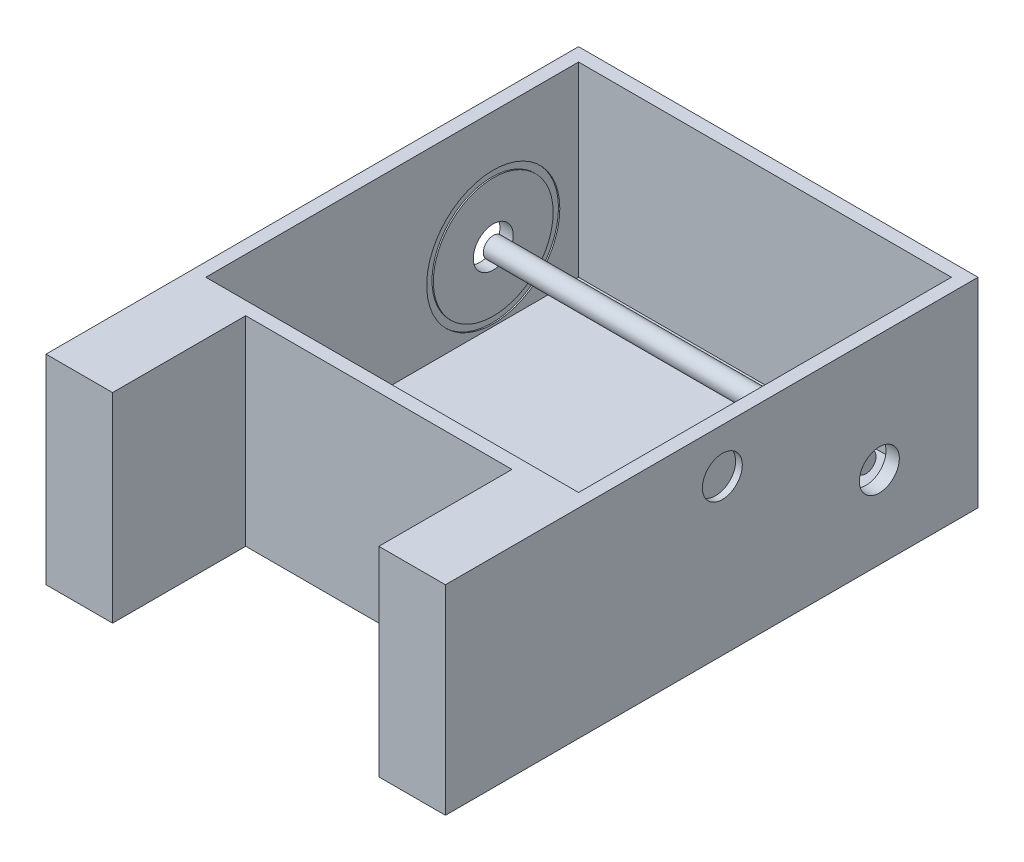
SolidWorks part; units mm, degrees
ref_plane "Front Plane" through (0, 0, 0) normal (0, 0, 1) x (1, 0, 0)
ref_plane "Top Plane" through (0, 0, 0) normal (0, 1, 0) x (1, 0, 0)
ref_plane "Right Plane" through (0, 0, 0) normal (1, 0, 0) x (0, 0, -1)
sketch "Sketch1" plane through (0, 0, 0) normal (0, 0, 1) x (1, 0, 0)
  line L1 (-150, -75) -> (150, -75)
  line L2 (-150, -75) -> (-150, 75)
  line L3 (-150, 75) -> (150, 75)
  line L4 (150, -75) -> (150, 75)
  line L5 (-150, -75) -> (150, 75) construction
  line L6 (-150, 75) -> (150, -75) construction
  point P0 (0, 0)
  dimension "D1" = 300
  dimension "D2" = 150
extrude "Boss-Extrude1" add sketch "Sketch1" along normal blind 300
shell "Shell1" thickness 10
sketch "Sketch2" plane through (-140, 0, 0) normal (1, 0, 0) x (0, 0, -1)
  circle A0 centre (-74.0856, -13.2578) radius 50
  circle A1 centre (-74.0856, -13.2578) radius 45
  point P2 (-68.2689, -30.7686)
  point P3 (0, 0)
  point P4 (-60.4517, -21.5698)
  point P6 (-74.1193, -23.3646)
  point P7 (-74.0856, -13.2578)
  dimension "D1" = 100
  dimension "D2" = 90
extrude "Cut-Extrude2" cut sketch "Sketch2" against normal blind 1 and the other way blind 284
sketch "Sketch8" plane through (-140, 0, 0) normal (1, 0, 0) x (0, 0, -1)
  circle A0 centre (-74.0856, -13.2578) radius 15
  dimension "D1" = 30
extrude "Cut-Extrude3" cut sketch "Sketch8" against normal blind 95 and the other way blind 361
sketch "Sketch9" plane through (-140, 0, 0) normal (1, 0, 0) x (0, 0, -1)
  circle A0 centre (-74.0856, -13.2578) radius 7.5
  dimension "D1" = 15
extrude "Boss-Extrude2" add sketch "Sketch9" along normal blind 280 separate body
sketch "Sketch14" plane through (0, 0, 300) normal (0, 0, 1) x (1, 0, 0)
  line L0 (-150, -75) -> (150, -75) construction
  line L1 (-150, 75) -> (-100, 75)
  line L2 (-150, 75) -> (-150, -75)
  line L3 (-150, -75) -> (-100, -75)
  line L4 (-100, 75) -> (-100, -75)
  line L6 (150, 75) -> (100, 75)
  line L7 (150, 75) -> (150, -75)
  line L8 (150, -75) -> (100, -75)
  line L9 (100, 75) -> (100, -75)
  dimension "D1" = 50
  dimension "D2" = 50
extrude "Boss-Extrude4" add sketch "Sketch14" along normal blind 100
sketch "Sketch15" plane through (150, 0, 0) normal (1, 0, 0) x (0, 0, -1)
  circle A0 centre (-192.0162, 41.4549) radius 15
extrude "Cut-Extrude6" cut sketch "Sketch15" against normal blind 5
